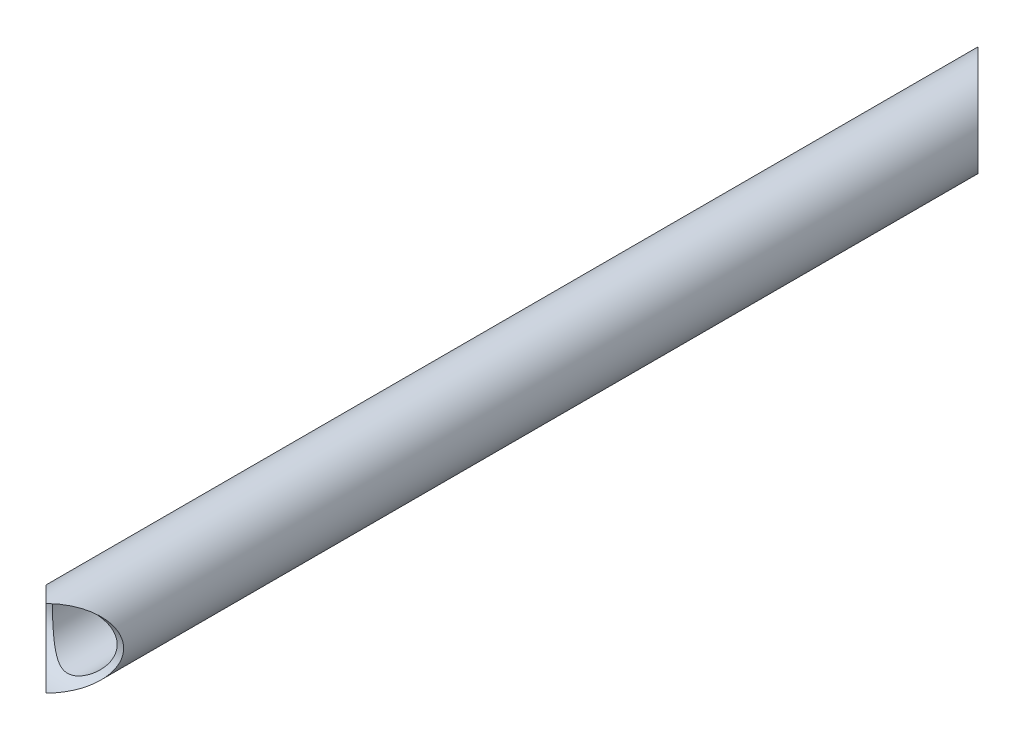
SolidWorks part; units mm, degrees
ref_plane "Front" through (0, 0, 0) normal (0, 0, 1) x (1, 0, 0)
ref_plane "Top" through (0, 0, 0) normal (0, 1, 0) x (1, 0, 0)
ref_plane "Right" through (0, 0, 0) normal (1, 0, 0) x (0, 0, -1)
sketch "Эскиз1" plane through (0, 0, 0) normal (0, 1, 0) x (1, 0, 0)
  line L0 (0, 0) -> (0, -375)
  dimension "D1" = 375
sketch "Эскиз2" plane through (0, 0, 0) normal (0, 0, 1) x (1, 0, 0)
  circle A0 centre (0, 0) radius 15
  dimension "D1" = 30
sweep "По траектории1" add profiles "Эскиз2" path "Эскиз1"
sketch "Эскиз3" plane through (0, 0, 375) normal (0, 0, 1) x (1, 0, 0)
  circle A0 centre (0, 0) radius 12.5
  circle A1 centre (0, 0) radius 15 construction
  dimension "D1" = 2.5
extrude "Вырез-Вытянуть1" cut sketch "Эскиз3" against normal through all
sketch "Эскиз4" plane through (0, 0, 0) normal (0, 1, 0) x (1, 0, 0)
  line L0 (-15, 0) -> (15, -30)
  line L1 (15, -375) -> (15, 0) construction
  line L2 (15, -30) -> (15, 0)
  line L3 (15, 0) -> (-15, 0) construction
  line L4 (15, 0) -> (-15, 0)
extrude "Вырез-Вытянуть2" cut sketch "Эскиз4" against normal through all and the other way through all
sketch "Эскиз5" plane through (0, 0, 0) normal (1, 0, 0) x (0, 0, -1)
  line L0 (-375, 15) -> (-375, -15)
  arc A0 (-375, 15) -> (-375, -15) centre (-375, 0) cw
  dimension "D1" = 15
extrude "Вырез-Вытянуть4" cut sketch "Эскиз5" against normal through all and the other way through all
sketch "для сборки" plane through (-7.5, 0, 7.5) normal (0.7071, 0, -0.7071) x (-0.7071, 0, -0.7071)
  ellipse E1 centre (-10.6066, 0) end of major axis (-28.2843, 0) minor radius 12.5 construction
  point P0 (-10.6066, 0)
